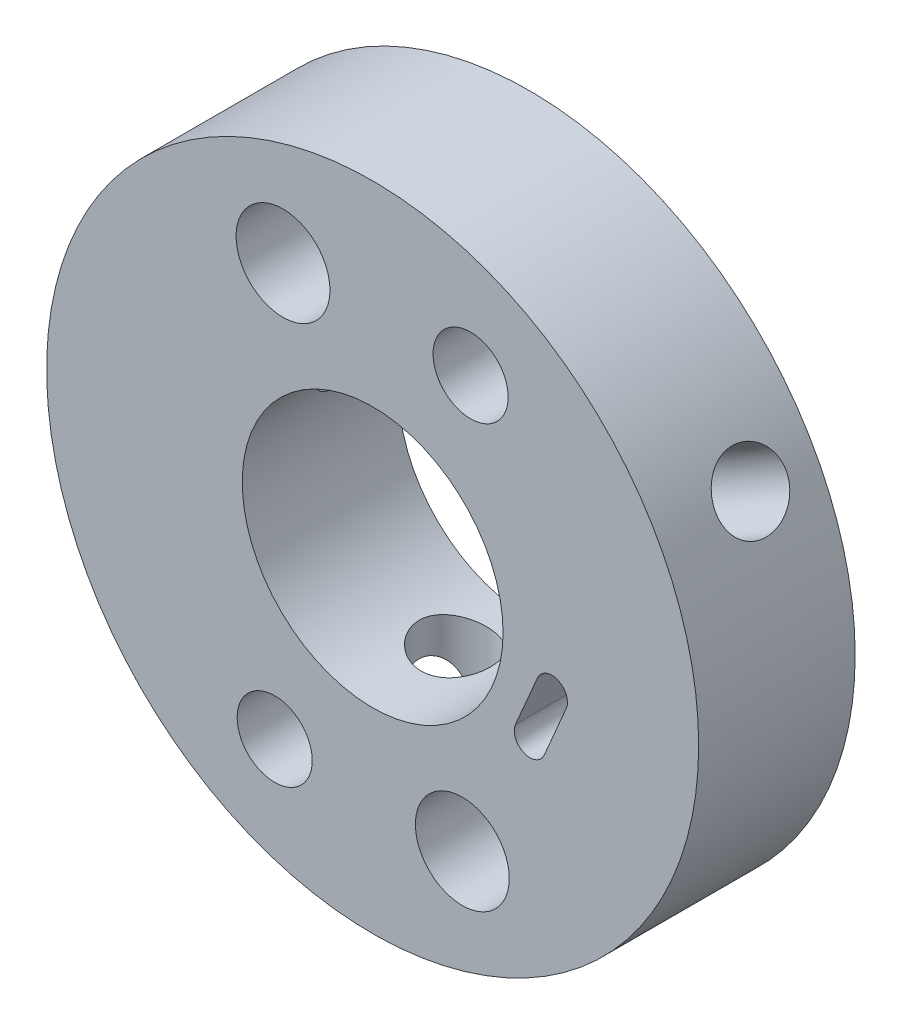
SolidWorks part; units mm, degrees
ref_plane "Front Plane" through (0, 0, 0) normal (0, 0, 1) x (1, 0, 0)
ref_plane "Top Plane" through (0, 0, 0) normal (0, 1, 0) x (1, 0, 0)
ref_plane "Right Plane" through (0, 0, 0) normal (1, 0, 0) x (0, 0, -1)
sketch "Sketch1" plane through (0, 0, 0) normal (0, 0, 1) x (1, 0, 0)
  circle A0 centre (0, 0) radius 15.875
  dimension "D1" = 31.75
extrude "Boss-Extrude1" add sketch "Sketch1" along normal blind 7.62
sketch "Sketch2" plane through (0, 0, 7.62) normal (0, 0, 1) x (1, 0, 0)
  circle A0 centre (0, 0) radius 6.35
  dimension "D1" = 12.7
extrude "Cut-Extrude1" cut sketch "Sketch2" against normal through all
ref_plane "Plane1" through (0, 0, 3.81) normal (0, 0, 1) x (1, 0, 0)
sketch "Sketch11" plane through (0, 0, 3.81) normal (0, 0, 1) x (1, 0, 0)
  point P0 (-31.3984, 15.2938)
  point P1 (31.3893, 15.3123)
  point P3 (0, -34.925)
sketch "Sketch33" plane through (0, 0, 7.62) normal (0, 0, 1) x (1, 0, 0)
  line L0 (-7.6406, 13.9153) -> (7.6406, -13.9153)
  circle A0 centre (0, 0) radius 15.875 construction
sketch "Sketch34" plane through (0, 0, 7.62) normal (0, 0, 1) x (1, 0, 0)
  line L0 (7.6406, -13.9153) -> (3.048, -5.5707)
  line L1 (-7.6406, 13.9153) -> (-10.7006, 19.4883)
  circle A0 centre (0, 0) radius 6.35 construction
  point P8 (5.3443, -9.743)
  point P9 (-9.1706, 16.7018)
ref_plane "Plane2" through (0, -15.875, 0) normal (0, -1, 0) x (-1, 0, 0)
hole_wizard "Tap Drill for #8-32 Tap1" positions "Sketch35" profile "Sketch36" hole size "#8-32" standard "ANSI Inch"
sketch "Sketch35" plane through (0, -15.875, 0) normal (0, -1, 0) x (-1, 0, 0)
  line L0 (17.4625, -3.175) -> (-17.4625, -3.175) construction
  point P0 (0.4504, -3.175)
sketch "Sketch36" plane through (-0.4504, -15.875, 3.175) normal (1, 0, 0) x (0, 0, -1)
  line L0 (0, 0) -> (0, 20.4993)
  line L1 (0, 20.4993) -> (1.7272, 19.05)
  line L2 (1.7272, 19.05) -> (1.7272, 0)
  line L5 (1.7272, 0) -> (0, 0)
  line L10 (0, 20.4993) -> (-1.7272, 19.05) construction
  line L11 (0, -6.35) -> (0, 107.95) construction
  dimension "Hole Dia." = 3.4544
  dimension "Hole Depth" = 19.05
  dimension "Drill Angle" = 100
pattern_circular "CirPattern1" count 3 over 360 about axis through (0, 0, 7.62) along (0, 0, -1) of "Tap Drill for #8-32 Tap1"
sketch "Sketch37" plane through (0, 0, 0) normal (0, 0, -1) x (-1, 0, 0)
  line L0 (0, 0) -> (-12.587, -13.4418)
  dimension "D2" = 18.415
sketch "Sketch38" plane through (0, 0, 0) normal (0, 0, -1) x (-1, 0, 0)
  line L0 (0, 0) -> (-6.4423, 9.0545)
  dimension "D1" = 11.1125
ref_point "Point1"
sketch "Sketch39" plane through (0, 0, 0) normal (0, 0, -1) x (-1, 0, 0)
  line L0 (0, 0) -> (4.7696, -10.0509)
  dimension "D1" = 11.1252
hole_wizard "CBORE for #6 Socket Head Cap Screw1" positions "Sketch40" profile "Sketch41" counterbore size "#6" standard "ANSI Inch" end condition through all
sketch "Sketch40" plane through (0, 0, 0) normal (0, 0, -1) x (-1, 0, 0)
  point P0 (4.7696, -10.0509)
sketch "Sketch41" plane through (-4.7696, -10.0509, 0) normal (1, 0, 0) x (0, 1, 0)
  line L0 (0, 0) -> (0, 7.62)
  line L1 (0, 7.62) -> (1.8288, 7.62)
  line L3 (1.8288, 7.62) -> (1.8288, 3.5052)
  line L4 (1.8288, 3.5052) -> (3.5725, 3.5052)
  line L5 (3.5725, 3.5052) -> (3.5725, 0)
  line L7 (3.5725, 0) -> (0, 0)
  line L11 (0, -6.35) -> (0, 107.95) construction
  dimension "Thru Hole Dia." = 3.6576
  dimension "Thru Hole Depth" = 7.62
  dimension "C'Bore Dia." = 7.145
  dimension "C'Bore Depth" = 3.5052
pattern_circular "CirPattern2" count 2 over 360 about axis through (0, 0, 0) along (0, 0, 1) of "CBORE for #6 Socket Head Cap Screw1"
sketch "Sketch42" plane through (0, 0, 0) normal (0, 0, -1) x (-1, 0, 0)
  line L0 (0, 0) -> (4.3654, 10.2192)
  circle A0 centre (4.3654, 10.2192) radius 2.286
extrude "Cut-Extrude2" cut sketch "Sketch42" against normal blind 7.62 contours A0
pattern_circular "CirPattern3" count 2 over 360 about axis through (0, 0, 0) along (0, 0, 1) of "Cut-Extrude2"
sketch "Sketch43" plane through (0, 0, 0) normal (0, 0, -1) x (-1, 0, 0)
  line L0 (-8.7244, -1.373) -> (-7.6557, -3.8635)
  line L1 (-8.7244, -1.373) -> (-7.6557, -3.8635) construction
  line L2 (-8.0257, -1.0731) -> (-6.957, -3.5637)
  line L3 (-9.4232, -1.6728) -> (-8.3545, -4.1634)
  arc A0 (-8.0257, -1.0731) -> (-9.4232, -1.6728) centre (-8.7244, -1.373) ccw
  arc A1 (-8.3545, -4.1634) -> (-6.957, -3.5637) centre (-7.6557, -3.8635) ccw
  point P2 (-8.1901, -2.6183)
  dimension "D1" = 2.7102
extrude "Cut-Extrude3" cut sketch "Sketch43" against normal through all contours L3 A1 L2 A0
ref_plane "Plane3" through (0, 0, 3.175) normal (0, 0, -1) x (-1, 0, 0)
